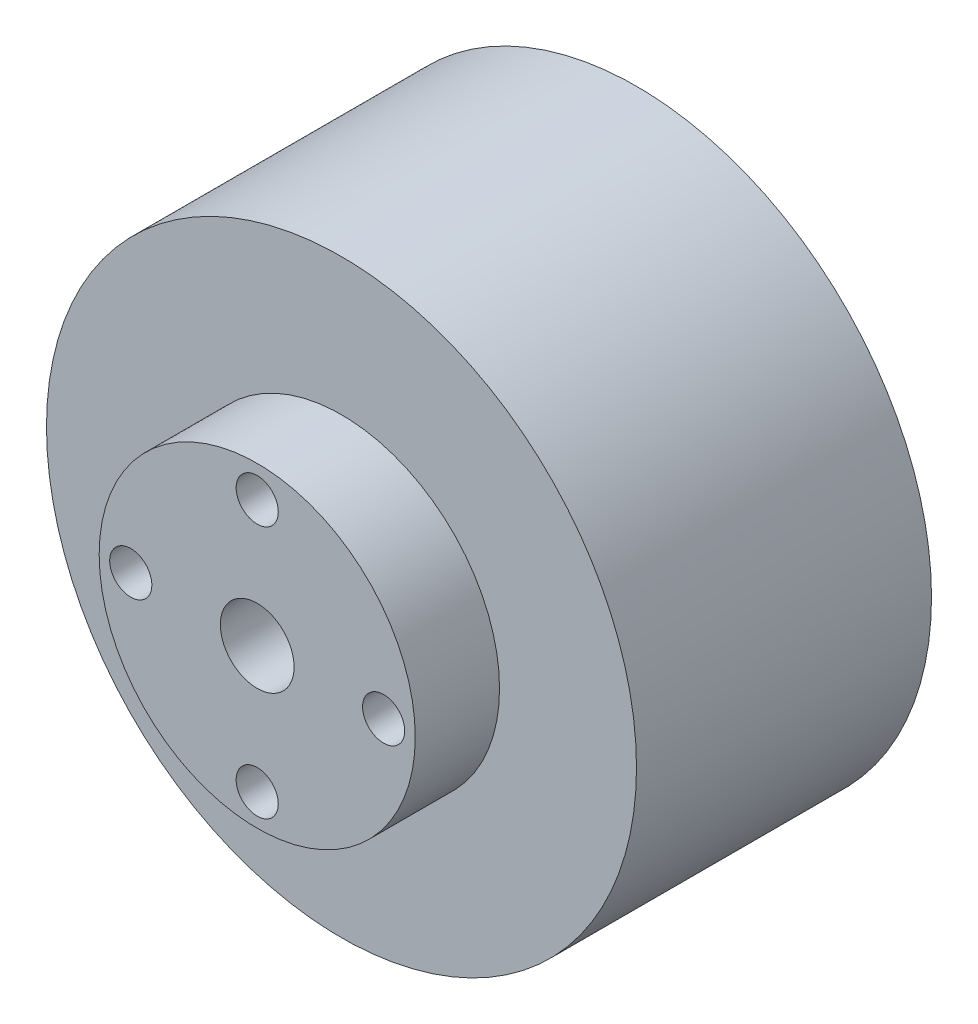
SolidWorks part; units mm, degrees
ref_plane "前视基准面" through (0, 0, 0) normal (0, 0, 1) x (1, 0, 0)
ref_plane "上视基准面" through (0, 0, 0) normal (0, 1, 0) x (1, 0, 0)
ref_plane "右视基准面" through (0, 0, 0) normal (1, 0, 0) x (0, 0, -1)
sketch "草图1" plane through (0, 0, 0) normal (0, 0, 1) x (1, 0, 0)
  circle A0 centre (0, 0) radius 14
  dimension "D1" = 28
extrude "凸台-拉伸1" add sketch "草图1" along normal blind 14
sketch "草图3" plane through (0, 0, 14) normal (0, 0, 1) x (1, 0, 0)
  circle A0 centre (0, 0) radius 7.5
  dimension "D1" = 15
extrude "凸台-拉伸3" add sketch "草图3" along normal blind 4
sketch "草图4" plane through (0, 0, 18) normal (0, 0, 1) x (1, 0, 0)
  circle A0 centre (0, 0) radius 1.75
  dimension "D1" = 3.5
extrude "切除-拉伸1" cut sketch "草图4" against normal through all
sketch "草图5" plane through (0, 0, 18) normal (0, 0, 1) x (1, 0, 0)
  line L0 (-17.4028, 0) -> (19.2585, 0) construction
  line L1 (0, 18.129) -> (0, -19.9613) construction
  circle A0 centre (0, -6) radius 1
  circle A1 centre (-6, 0) radius 1
  circle A2 centre (0, 6) radius 1
  circle A3 centre (6, 0) radius 1
  dimension "D1" = 2
  dimension "D2" = 6
  dimension "D3" = 6
  dimension "D4" = 6
  dimension "D5" = 6
extrude "切除-拉伸2" cut sketch "草图5" against normal blind 3 contours A3 | A1 | A0 | A2
sketch "草图6" plane through (0, 0, 0) normal (0, 0, 1) x (1, 0, 0)
  line L0 (24.9097, 0) -> (-28.6773, 0) construction
  line L1 (0, 19.7976) -> (0, -23.3744) construction
  circle A0 centre (0, 8) radius 1.5
  circle A1 centre (-8, 0) radius 1.5
  circle A2 centre (0, -8) radius 1.5
  circle A3 centre (8, 0) radius 1.5
  point P15 (0, -7.6563)
  dimension "D1" = 3
  dimension "D2" = 8
  dimension "D3" = 8
  dimension "D4" = 8
  dimension "D5" = 8
extrude "切除-拉伸3" cut sketch "草图6" along normal blind 3
